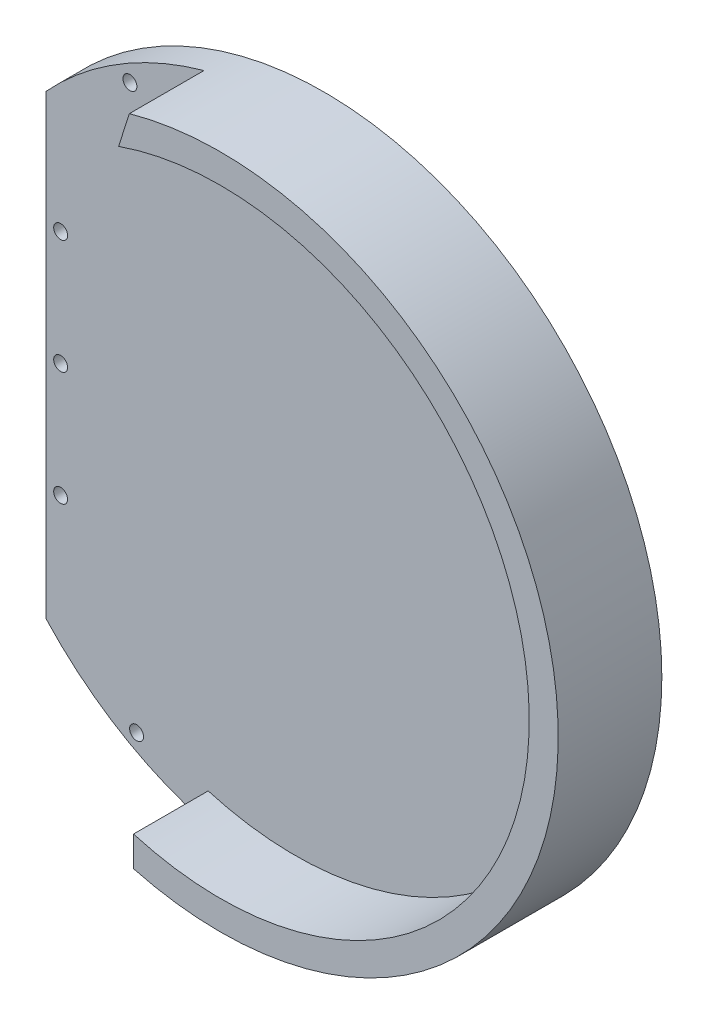
SolidWorks part; units mm, degrees
ref_plane "Front Plane" through (0, 0, 0) normal (0, 0, 1) x (1, 0, 0)
ref_plane "Top Plane" through (0, 0, 0) normal (0, 1, 0) x (1, 0, 0)
ref_plane "Right Plane" through (0, 0, 0) normal (1, 0, 0) x (0, 0, -1)
sketch "Sketch1" plane through (0, 0, 0) normal (0, 0, 1) x (1, 0, 0)
  line L0 (0, -39.4175) -> (0, 39.4175)
  arc A0 (0, 39.4175) -> (0, -39.4175) centre (42.9355, 0) cw
  point P4 (0, 0)
  point P6 (101.221, 0)
  dimension "D1" = 78.835
  dimension "D2" = 101.221
extrude "Boss-Extrude1" add sketch "Sketch1" along normal blind 5
sketch "Sketch2" plane through (0, 0, 5) normal (0, 0, 1) x (1, 0, 0)
  line L0 (0, 39.4175) -> (0, -39.4175) construction
  line L1 (0, 39.4175) -> (0, -39.4175) construction
  line L2 (5, 37.4198) -> (5, -37.4198) construction
  line L3 (0, 39.4175) -> (21.901, 39.4175) construction
  line L4 (21.901, 39.4175) -> (27.2366, 56.1315) construction
  line L5 (0, 0) -> (5, 0) construction
  line L6 (2.5, 41.9782) -> (2.5, -41.9782) construction
  line L7 (2.5, 0) -> (2.5, 39.4175) construction
  line L8 (2.5, -39.4175) -> (2.5, 0) construction
  line L9 (14.4504, 45.0327) -> (14.4504, 50.8507) construction
  line L10 (27.955, -51.1364) -> (27.955, -56.3275) construction
  line L11 (15.6031, -45.7414) -> (15.6031, -51.4795) construction
  arc A0 (0, -39.4175) -> (0, 39.4175) centre (42.9355, 0) ccw construction
  arc A1 (0, -39.4175) -> (0, 39.4175) centre (42.9355, 0) ccw construction
  arc A2 (5, -37.4198) -> (5, 37.4198) centre (42.9355, 0) ccw construction
  circle A3 centre (2.5, 19.7088) radius 1.2
  circle A4 centre (2.5, 0) radius 1.2
  circle A5 centre (2.5, -19.7087) radius 1.2
  circle A6 centre (14.4504, 47.9417) radius 1.2
  circle A7 centre (15.6031, -48.6105) radius 1.2
  arc A8 (5, 37.4198) -> (25.3782, 50.3099) centre (42.9355, 0) cw construction
  arc A9 (5, -37.4198) -> (27.955, -51.1364) centre (42.9355, 0) ccw construction
  point P14 (2.5, 0)
  point P24 (2.5, 0)
  dimension "D1" = 5
  dimension "D4" = 2.4
  dimension "D2" = 21.901
  dimension "D3" = 107.705
  dimension "D5" = 27.955
extrude "Cut-Extrude1" cut sketch "Sketch2" against normal through all
sketch "Sketch3" plane through (0, 0, 5) normal (0, 0, 1) x (1, 0, 0)
  line L0 (27.955, -56.3275) -> (27.955, -51.1364)
  line L1 (25.3782, 50.3099) -> (27.2366, 56.1315)
  arc A0 (25.3782, 50.3099) -> (27.955, -51.1364) centre (42.9355, 0) cw
  arc A1 (27.955, -56.3275) -> (27.2366, 56.1315) centre (42.9355, 0) ccw
  arc A2 (5, -37.4198) -> (5, 37.4198) centre (42.9355, 0) ccw construction
  arc A3 (0, -39.4175) -> (0, 39.4175) centre (42.9355, 0) ccw construction
extrude "Boss-Extrude2" add sketch "Sketch3" along normal blind 12.879
equation "\"width\"=0.101221"
equation "\"height\"=0.078835"
equation "\"stop_width\"=0.005000"
equation "\"inf_stop_x\"=0.027955"
equation "\"superior_stop_x\"=0.021901"
equation "\"superior_stop_angle\"=107.704683"
equation "\"t1\"=0.005000"
equation "\"t2\"=0.012879"
equation "\"cover_holes_diam\"=0.002400"
equation "\"cover_holes_depth\"=0.004000"
equation "\"cover_hole_pitch\"=0.000400"
equation "\"D1@Sketch1\"=\"height\"*1000"
equation "\"D2@Sketch1\"=\"width\"*1000"
equation "\"D1@Boss-Extrude1\"=\"t1\"*1000"
equation "\"D1@Sketch2\"=\"stop_width\"*1000"
equation "\"D2@Sketch2\"=\"superior_stop_x\"*1000"
equation "\"D3@Sketch2\"=\"superior_stop_angle\""
equation "\"D4@Sketch2\"=\"cover_holes_diam\"*1000"
equation "\"D5@Sketch2\"=\"inf_stop_x\"*1000"
equation "\"D1\"= \"cover_holes_depth\" * 1000"
equation "\"D1@Boss-Extrude2\"=\"t2\"*1000"
